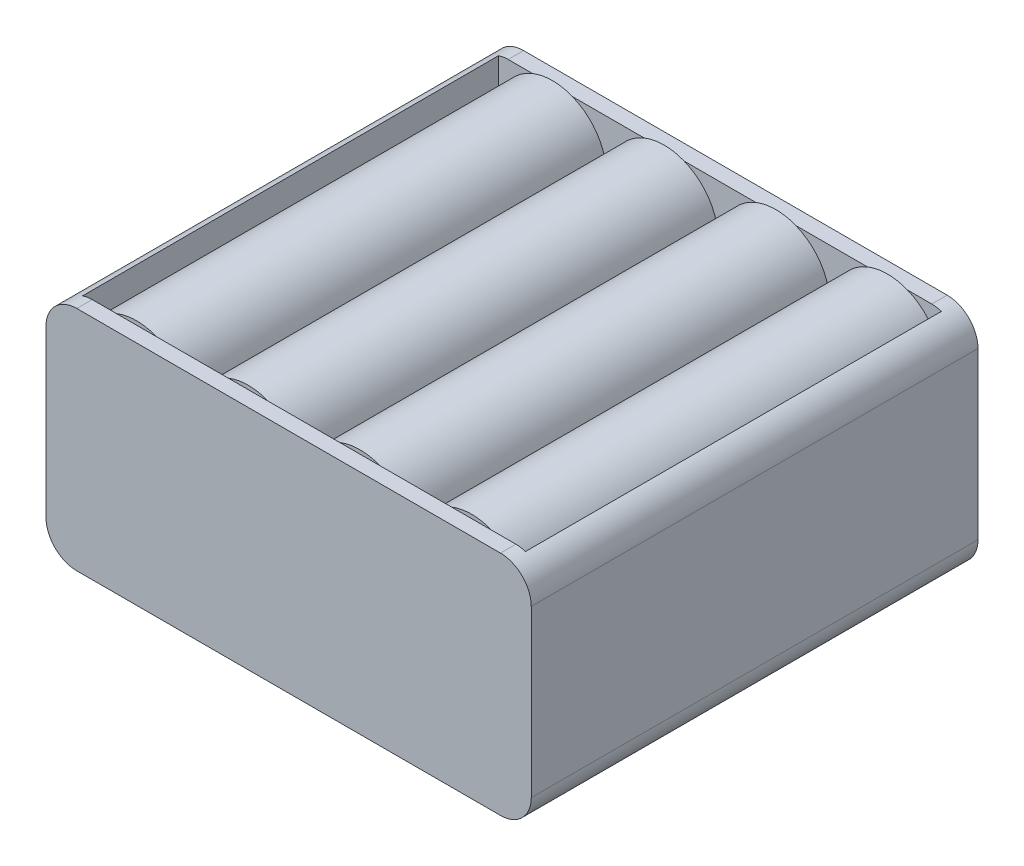
SolidWorks part; units mm, degrees
ref_plane "Front Plane" through (0, 0, 0) normal (0, 0, 1) x (1, 0, 0)
ref_plane "Top Plane" through (0, 0, 0) normal (0, 1, 0) x (1, 0, 0)
ref_plane "Right Plane" through (0, 0, 0) normal (1, 0, 0) x (0, 0, -1)
sketch "Sketch1" plane through (0, 0, 0) normal (0, 1, 0) x (1, 0, 0)
  line L1 (-31.5, 29) -> (31.5, 29)
  line L2 (-31.5, 29) -> (-31.5, -29)
  line L3 (-31.5, -29) -> (31.5, -29)
  line L4 (31.5, 29) -> (31.5, -29)
  line L5 (-31.5, 29) -> (31.5, -29) construction
  line L6 (-31.5, -29) -> (31.5, 29) construction
  point P0 (0, 0)
  dimension "D1" = 58
  dimension "D2" = 63
extrude "Boss-Extrude1" add sketch "Sketch1" along normal blind 29.5
fillet "Fillet1" radius 4 4 edges at (31.5, 0, 0) (-31.5, 0, 0) (-31.5, 29.5, 0) (31.5, 29.5, 0)
sketch "Sketch2" plane through (0, 0, 0) normal (0, 0, 1) x (1, 0, 0)
  line L0 (-21.75, 23) -> (-7.25, 23) construction
  line L1 (-7.25, 23) -> (7.25, 23) construction
  line L2 (7.25, 23) -> (21.75, 23) construction
  line L3 (21.75, 23) -> (21.75, 6.5) construction
  line L4 (21.75, 6.5) -> (7.25, 6.5) construction
  line L5 (7.25, 6.5) -> (-7.25, 6.5) construction
  line L6 (-7.25, 6.5) -> (-21.75, 6.5) construction
  line L7 (-21.75, 6.5) -> (-21.75, 23) construction
  line L8 (-21.75, 14.75) -> (-31.5, 14.75) construction
  line L9 (21.75, 14.75) -> (31.5, 14.75) construction
  line L10 (31.5, 25.5) -> (31.5, 4) construction
  line L11 (-31.5, 25.5) -> (-31.5, 4) construction
  line L18 (-14.75, 23) -> (-14.25, 23)
  line L19 (-0.25, 23) -> (0.25, 23)
  line L20 (14.25, 23) -> (14.75, 23)
  line L21 (-14.75, 6.5) -> (-14.25, 6.5)
  line L22 (-0.25, 6.5) -> (0.25, 6.5)
  line L23 (14.25, 6.5) -> (14.75, 6.5)
  line L24 (-28.75, 23) -> (-28.75, 32.8903)
  line L25 (-28.75, 32.8903) -> (28.75, 32.8903)
  line L26 (28.75, 32.8903) -> (28.75, 23)
  line L27 (28.75, 6.5) -> (28.75, -3.9994)
  line L28 (28.75, -3.9994) -> (-28.75, -3.472)
  line L29 (-28.75, -3.472) -> (-28.75, 6.5)
  arc A0 (-14.75, 23) -> (-28.75, 23) centre (-21.75, 23) ccw
  arc A1 (-0.25, 23) -> (-14.25, 23) centre (-7.25, 23) ccw
  arc A2 (14.25, 23) -> (0.25, 23) centre (7.25, 23) ccw
  arc A3 (28.75, 23) -> (14.75, 23) centre (21.75, 23) ccw
  arc A4 (14.75, 6.5) -> (28.75, 6.5) centre (21.75, 6.5) ccw
  arc A5 (0.25, 6.5) -> (14.25, 6.5) centre (7.25, 6.5) ccw
  arc A6 (-14.25, 6.5) -> (-0.25, 6.5) centre (-7.25, 6.5) ccw
  arc A7 (-28.75, 6.5) -> (-14.75, 6.5) centre (-21.75, 6.5) ccw
  dimension "D1" = 14
  dimension "D3" = 30.5
  dimension "D2" = 14.5
extrude "Cut-Extrude1" cut sketch "Sketch2" against normal mid plane 54
sketch "Sketch3" plane through (0, 0, 0) normal (0, 0, 1) x (1, 0, 0)
  circle A0 centre (-21.75, 23) radius 7
  circle A1 centre (-7.25, 23) radius 7
  circle A2 centre (7.25, 23) radius 7
  circle A3 centre (21.75, 23) radius 7
  circle A4 centre (21.75, 6.5) radius 7
  circle A5 centre (7.25, 6.5) radius 7
  circle A6 centre (-7.25, 6.5) radius 7
  circle A7 centre (-21.75, 6.5) radius 7
  arc A8 (-28.75, 6.5) -> (-14.75, 6.5) centre (-21.75, 6.5) ccw construction
  arc A9 (-14.25, 6.5) -> (-0.25, 6.5) centre (-7.25, 6.5) ccw construction
  arc A10 (0.25, 6.5) -> (14.25, 6.5) centre (7.25, 6.5) ccw construction
  arc A11 (14.75, 6.5) -> (28.75, 6.5) centre (21.75, 6.5) ccw construction
  arc A12 (28.75, 23) -> (14.75, 23) centre (21.75, 23) ccw construction
  arc A13 (14.25, 23) -> (0.25, 23) centre (7.25, 23) ccw construction
  arc A14 (-0.25, 23) -> (-14.25, 23) centre (-7.25, 23) ccw construction
  arc A15 (-14.75, 23) -> (-28.75, 23) centre (-21.75, 23) ccw construction
extrude "Boss-Extrude2" add sketch "Sketch3" along normal mid plane 54
sketch "Sketch4" plane through (0, 0, -29) normal (0, 0, -1) x (-1, 0, 0)
  line L0 (-27.5, 0) -> (27.5, 0) construction
  line L1 (28.5, 15) -> (4.5, 15)
  line L2 (31.5, 12) -> (31.5, 3)
  line L3 (28.5, 0) -> (4.5, 0)
  line L4 (1.5, 12) -> (1.5, 3)
  line L5 (31.5, 15) -> (1.5, 0) construction
  line L6 (31.5, 0) -> (1.5, 15) construction
  line L7 (31.5, 25.5) -> (31.5, 4) construction
  arc A0 (4.5, 15) -> (1.5, 12) centre (4.5, 12) ccw
  arc A1 (4.5, 0) -> (1.5, 3) centre (4.5, 3) cw
  arc A2 (31.5, 3) -> (28.5, 0) centre (28.5, 3) cw
  arc A3 (28.5, 15) -> (31.5, 12) centre (28.5, 12) cw
  point P0 (16.5, 7.5)
  dimension "D3" = 3
  dimension "D1" = 15
  dimension "D2" = 30
extrude "Boss-Extrude3" add sketch "Sketch4" along normal blind 7
